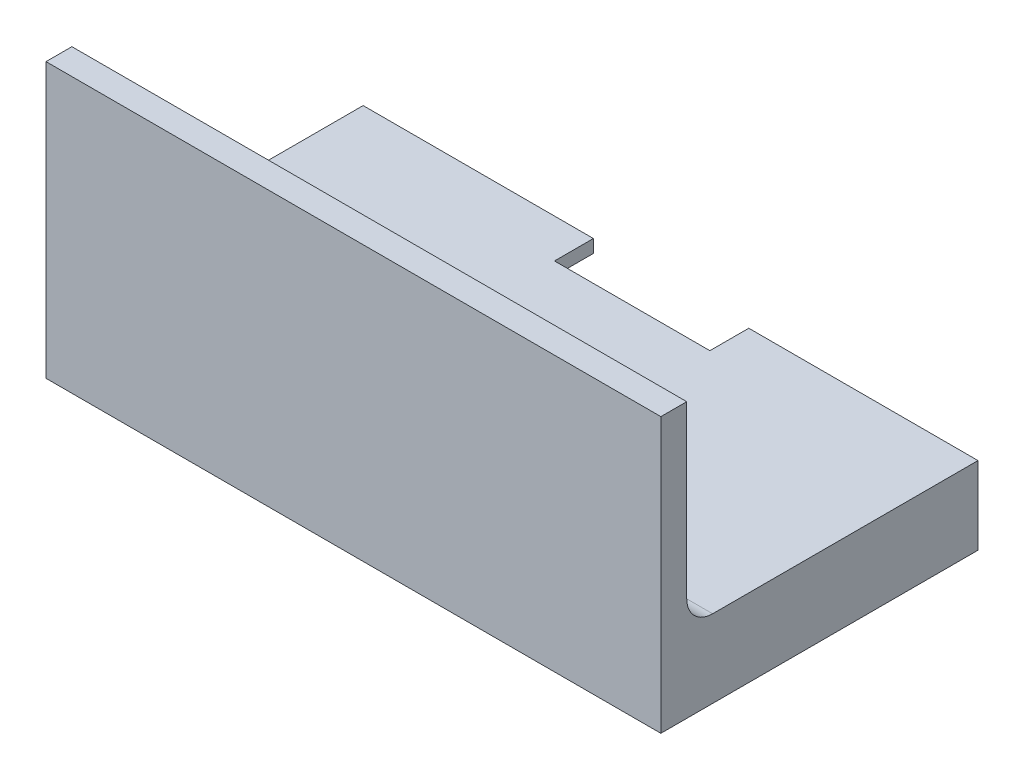
SolidWorks part; units mm, degrees
ref_plane "Front Plane" through (0, 0, 0) normal (0, 0, 1) x (1, 0, 0)
ref_plane "Top Plane" through (0, 0, 0) normal (0, 1, 0) x (1, 0, 0)
ref_plane "Right Plane" through (0, 0, 0) normal (1, 0, 0) x (0, 0, -1)
sketch "Sketch3" plane through (0, 0, 0) normal (0, 1, 0) x (1, 0, 0)
  line L1 (-79.8619, 6.7352) -> (-32.3619, 6.7352)
  line L2 (-79.8619, 6.7352) -> (-79.8619, -15.7648)
  line L3 (-79.8619, -15.7648) -> (-32.3619, -15.7648)
  line L4 (-32.3619, 6.7352) -> (-32.3619, -15.7648)
extrude "Boss-Extrude1" add sketch "Sketch3" along normal blind 6 contours L1 L4 L3 L2
sketch "Sketch74" plane through (0, 6, 0) normal (0, 1, 0) x (1, 0, 0)
  line L1 (-62.0739, 6.7352) -> (-50.0697, 6.7352)
  line L2 (-79.8619, 6.7352) -> (-32.3619, 6.7352) construction
  line L4 (-62.0739, 4.7352) -> (-62.0739, 6.7352)
  line L5 (-62.0739, 6.7352) -> (-50.0697, 6.7352)
  line L6 (-50.0697, 4.7352) -> (-50.0697, 6.7352)
  line L7 (-62.0739, 4.7352) -> (-50.0697, 6.7352) construction
  line L8 (-62.0739, 6.7352) -> (-50.0697, 4.7352) construction
  line L9 (-62.0739, 6.7352) -> (-62.0739, 3.7303)
  line L10 (-62.0739, 3.7303) -> (-50.0697, 3.7303)
  line L11 (-50.0697, 6.7352) -> (-50.0697, 3.7303)
  line L12 (-62.0739, 6.7352) -> (-50.0697, 3.7303) construction
  line L13 (-62.0739, 3.7303) -> (-50.0697, 6.7352) construction
  point P3 (-56.0718, 5.2328)
sketch "Sketch77" plane through (0, 6, 0) normal (0, 1, 0) x (1, 0, 0)
extrude "Cut-Extrude6" cut sketch "Sketch74" against normal blind 10 contours L9 L1 L11 L10
sketch "Sketch79" plane through (0, 0, 0) normal (0, 1, 0) x (1, 0, 0)
  line L0 (-79.8619, -15.7648) -> (-32.3619, -15.7648) construction
  line L1 (-79.8619, -15.7648) -> (-32.3619, -15.7648)
  line L2 (-79.8619, -15.7648) -> (-79.8619, -17.7648)
  line L3 (-79.8619, -17.7648) -> (-32.3619, -17.7648)
  line L4 (-32.3619, -15.7648) -> (-32.3619, -17.7648)
extrude "Boss-Extrude2" add sketch "Sketch79" along normal blind 21.1901
fillet "Fillet6" radius 2 1 edges at (-56.1119, 6, 15.7648)
sketch "Sketch82" plane through (0, 0, -6.7352) normal (0, 0, -1) x (-1, 0, 0)
  line L13 (78.8619, 1) -> (33.3619, 1)
  line L14 (78.8619, 1) -> (78.8619, 5)
  line L15 (78.8619, 5) -> (33.3619, 5)
  line L16 (33.3619, 1) -> (33.3619, 5)
extrude "Cut-Extrude7" cut sketch "Sketch82" against normal blind 20.5 contours L14 L13 L16 L15
sketch "Sketch84" plane through (0, 0, -6.7352) normal (0, 0, -1) x (-1, 0, 0)
  line L5 (78.8619, 1) -> (33.3619, 1) construction
  line L7 (78.8619, 1) -> (62.0739, 1) construction
  line L8 (62.0739, 0) -> (79.8619, 0) construction
  line L9 (34.3619, 1) -> (77.8619, 1)
  line L10 (34.3619, 1) -> (34.3619, 0)
  line L11 (34.3619, 0) -> (77.8619, 0)
  line L12 (77.8619, 1) -> (77.8619, 0)
extrude "Cut-Extrude8" cut sketch "Sketch84" against normal blind 20
